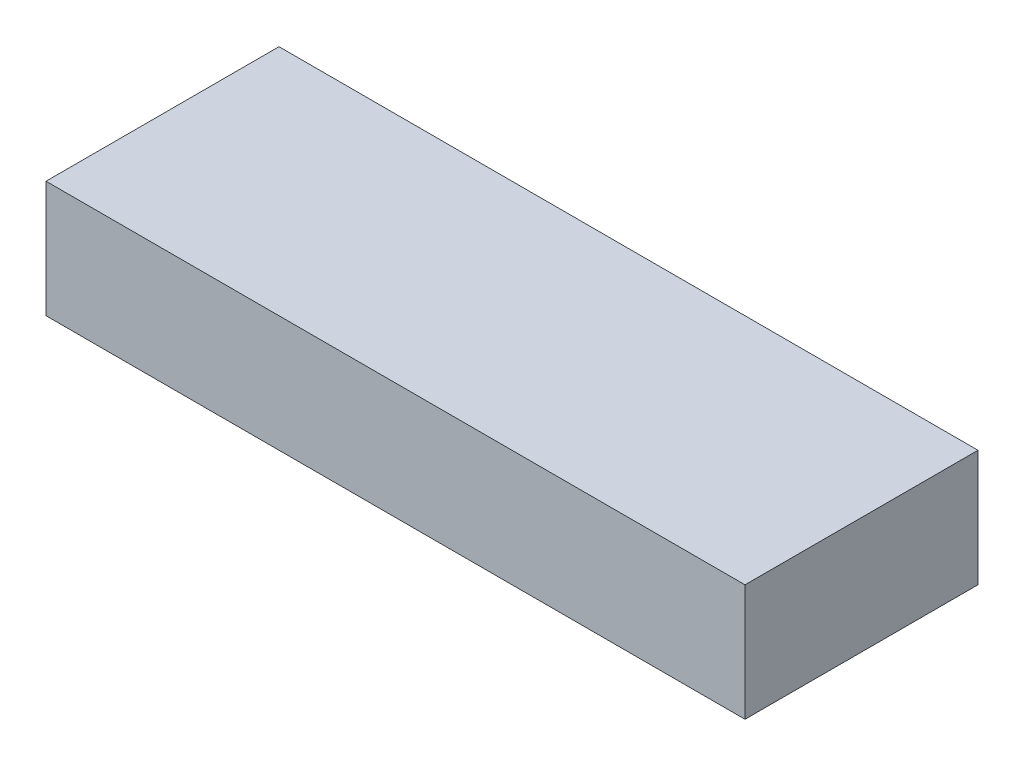
SolidWorks part; units mm, degrees
ref_plane "前视基准面" through (0, 0, 0) normal (0, 0, 1) x (1, 0, 0)
ref_plane "上视基准面" through (0, 0, 0) normal (0, 1, 0) x (1, 0, 0)
ref_plane "右视基准面" through (0, 0, 0) normal (1, 0, 0) x (0, 0, -1)
sketch "草图1" plane through (0, 0, 0) normal (0, 0, 1) x (1, 0, 0)
  line L1 (-5.2503, 2) -> (0.7497, 2)
  line L2 (-5.2503, 2) -> (-5.2503, 1)
  line L3 (-5.2503, 1) -> (0.7497, 1)
  line L4 (0.7497, 2) -> (0.7497, 1)
  dimension "D1" = 1
  dimension "D2" = 6
extrude "凸台-拉伸1" add sketch "草图1" along normal blind 2
